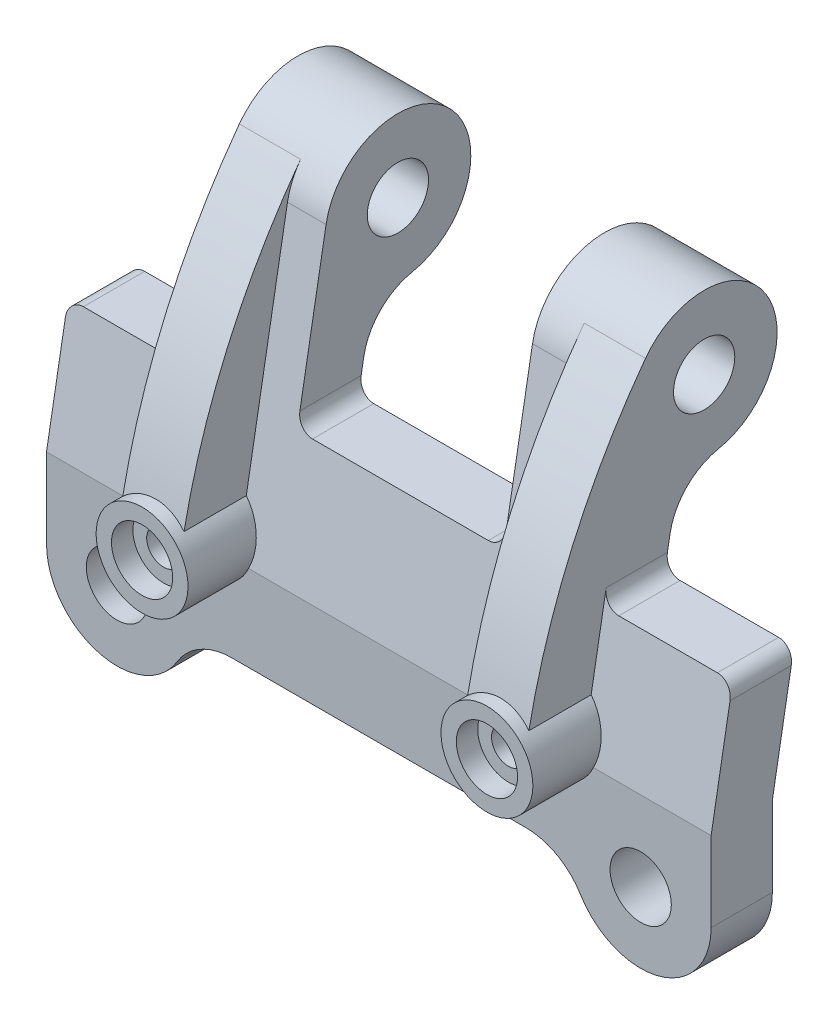
SolidWorks part; units mm, degrees
ref_plane "Front Plane" through (0, 0, 0) normal (0, 0, 1) x (1, 0, 0)
ref_plane "Top Plane" through (0, 0, 0) normal (0, 1, 0) x (1, 0, 0)
ref_plane "Right Plane" through (0, 0, 0) normal (1, 0, 0) x (0, 0, -1)
sketch "Sketch2" plane through (0, 0, 0) normal (1, 0, 0) x (0, 0, -1)
  line L0 (2.8983, 8.382) -> (0.3583, 8.382) construction
  line L1 (0.3583, 8.382) -> (0, 6.35)
  line L2 (0, 6.35) -> (0, 0)
  line L3 (0, 0) -> (2.54, 0)
  line L7 (2.8983, 8.382) -> (2.54, 6.35)
  line L8 (2.54, 6.35) -> (2.54, 0)
  line L9 (0.3583, 8.382) -> (2.9112, 22.86)
  line L10 (2.8983, 8.382) -> (5.4512, 22.86)
  line L11 (2.9112, 22.86) -> (5.4512, 22.86)
  point P3 (0, 0)
  dimension "D1" = 2.54
  dimension "D2" = 100
  dimension "D3" = 8.382
  dimension "D4" = 6.35
  dimension "D5" = 22.86
extrude "Boss-Extrude1" add sketch "Sketch2" along normal mid plane 27.559
sketch "Sketch3" plane through (0, 0, 0) normal (0, 0, 1) x (1, 0, 0)
  line L0 (-6.0931, 2.794) -> (6.0931, 2.794)
  line L2 (13.7795, 3.0391) -> (13.7795, 6.35) construction
  line L3 (13.7795, 6.35) -> (-13.7795, 6.35) construction
  line L4 (-13.7795, 6.35) -> (-13.7795, 3.0391) construction
  line L6 (13.7795, 22.86) -> (13.7795, 6.35) construction
  line L7 (-13.7795, 22.86) -> (-13.7795, 6.35) construction
  line L8 (0, 2.794) -> (0, 0) construction
  line L9 (13.7795, 0) -> (-13.7795, 0) construction
  line L10 (13.7795, 6.35) -> (-13.7795, 6.35) construction
  line L11 (-13.7795, 6.35) -> (-13.7795, 0) construction
  line L12 (10.8585, 3.0391) -> (13.7795, 3.0391) construction
  line L13 (13.7795, 3.0391) -> (14.4145, 3.0391)
  line L14 (14.4145, 3.0391) -> (14.4145, -0.635)
  line L15 (14.4145, -0.635) -> (-14.4145, -0.635)
  line L16 (-14.4145, -0.635) -> (-14.4145, 3.0391)
  line L17 (-14.4145, 3.0391) -> (-13.7795, 3.0391)
  line L18 (13.7795, 6.35) -> (13.7795, 0) construction
  line L19 (-14.4145, 11.43) -> (-8.4201, 11.43)
  line L20 (-8.4201, 11.43) -> (-8.4201, 22.86)
  line L21 (13.7795, 22.86) -> (-13.7795, 22.86) construction
  line L22 (-8.4201, 22.86) -> (-4.2799, 22.86)
  line L23 (-4.2799, 22.86) -> (-4.2799, 11.43)
  line L24 (-4.2799, 11.43) -> (4.2799, 11.43)
  line L25 (4.2799, 11.43) -> (4.2799, 22.86)
  line L26 (4.2799, 22.86) -> (8.4201, 22.86)
  line L27 (8.4201, 22.86) -> (8.4201, 11.43)
  line L28 (8.4201, 11.43) -> (14.4145, 11.43)
  line L29 (14.4145, 11.43) -> (14.4145, 23.495)
  line L30 (14.4145, 23.495) -> (-14.4145, 23.495)
  line L31 (-14.4145, 23.495) -> (-14.4145, 11.43)
  arc A0 (8.3645, 1.5186) -> (6.0931, 2.794) centre (6.0931, 0.1338) ccw
  arc A1 (8.3645, 1.5186) -> (13.7795, 3.0391) centre (10.8585, 3.0391) ccw
  arc A2 (-13.7795, 3.0391) -> (-8.3645, 1.5186) centre (-10.8585, 3.0391) ccw
  arc A3 (-6.0931, 2.794) -> (-8.3645, 1.5186) centre (-6.0931, 0.1338) ccw
  circle A4 centre (-10.8585, 3.0391) radius 1.27
  circle A5 centre (10.8585, 3.0391) radius 1.27
  dimension "D2" = 2.921
  dimension "D3" = 2.921
  dimension "D15" = 2.54
  dimension "D16" = 2.54
  dimension "D1" = 2.794
  dimension "D4" = 12.1862
  dimension "D5" = 3.3109
  dimension "D6" = 3.3109
  dimension "D7" = 0.635
  dimension "D8" = 0.635
  dimension "D9" = 0.635
  dimension "D10" = 0.635
  dimension "D11" = 5.3594
  dimension "D12" = 5.3594
  dimension "D13" = 4.1402
  dimension "D14" = 4.1402
  dimension "D17" = 8.636
extrude "Cut-Extrude1" cut sketch "Sketch3" against normal through all
sketch "Sketch4" plane through (0, 0, 0) normal (1, 0, 0) x (0, 0, -1)
  line L5 (0.8957, 11.43) -> (2.9112, 22.86) construction
  circle A0 centre (5.0709, 17.6911) radius 1.27 construction
  circle A3 centre (5.0709, 17.6911) radius 3.0245
  dimension "D2" = 2.5309
  dimension "D3" = 2.54
  dimension "D1" = 11.3411
extrude "Boss-Extrude3" add sketch "Sketch4" along normal up to surface and the other way up to surface contours A3 up to face at (13.7795, 6.9397, -1.5686) other way up to face at (-13.7795, 6.9397, -1.5686)
sketch "Sketch5" plane through (13.7795, 0, 0) normal (1, 0, 0) x (0, 0, -1)
  line L0 (2.0923, 18.2163) -> (2.9112, 22.86) construction
  line L1 (5.4512, 22.86) -> (5.073, 20.7156) construction
  line L2 (5.4512, 22.86) -> (2.9112, 22.86) construction
  line L3 (2.0923, 18.2163) -> (2.9112, 22.86)
  line L4 (5.4512, 22.86) -> (2.9112, 22.86)
  line L5 (5.4512, 22.86) -> (5.073, 20.7156)
  arc A0 (2.0923, 18.2163) -> (5.073, 20.7156) centre (5.0709, 17.6911) cw
  circle A2 centre (5.0709, 17.6911) radius 1.27
  dimension "D1" = 2.54
extrude "Cut-Extrude2" cut sketch "Sketch5" against normal blind 27.686
sketch "Sketch6" plane through (0, 0, 0) normal (0, 0, 1) x (1, 0, 0)
  line L0 (-8.4201, 18.2163) -> (-8.4201, 11.43) construction
  line L1 (-8.4201, 14.6666) -> (-13.7795, 14.6666)
  line L2 (-8.4201, 14.6666) -> (-8.4201, 20.7156)
  line L3 (-8.4201, 20.7156) -> (-13.7795, 20.7156)
  line L4 (-13.7795, 14.6666) -> (-13.7795, 20.7156)
  line L5 (-13.7795, 14.6666) -> (13.7795, 14.6666) construction
  line L6 (-4.2799, 11.43) -> (-4.2799, 18.2163) construction
  line L7 (-4.2799, 14.6666) -> (4.2799, 14.6666)
  line L8 (-4.2799, 14.6666) -> (-4.2799, 20.7156)
  line L9 (-4.2799, 20.7156) -> (4.2799, 20.7156)
  line L10 (4.2799, 14.6666) -> (4.2799, 20.7156)
  line L11 (13.7795, 20.7156) -> (-13.7795, 20.7156) construction
  line L12 (8.4201, 11.43) -> (8.4201, 18.2163) construction
  line L13 (8.4201, 14.6666) -> (13.7795, 14.6666)
  line L14 (8.4201, 14.6666) -> (8.4201, 20.7156)
  line L15 (8.4201, 20.7156) -> (13.7795, 20.7156)
  line L16 (13.7795, 14.6666) -> (13.7795, 20.7156)
  line L17 (4.2799, 18.2163) -> (4.2799, 14.8483) construction
extrude "Cut-Extrude3" cut sketch "Sketch6" against normal through all
fillet "Fillet1" radius 2.54 1 edges at (6.35, 14.8483, -4.0385)
sketch "Sketch7" plane through (-8.4201, 0, 0) normal (-1, 0, 0) x (0, 0, 1)
  line L1 (0, 6.35) -> (2.54, 6.35)
  line L2 (-2.0923, 18.2163) -> (0, 6.35)
  arc A0 (-2.6368, 19.4863) -> (2.54, 6.35) centre (-24.731, 3.1911) cw
  arc A1 (-2.0923, 18.2163) -> (-5.661, 14.7248) centre (-5.0709, 17.6911) ccw construction
  arc A2 (-2.0923, 18.2163) -> (-2.6368, 19.4863) centre (-5.0709, 17.6911) ccw
  point P0 (-2.6746, 19.2824)
  point P8 (0, 0)
  dimension "D1" = 2.54
  dimension "D2" = 1.27
extrude "Boss-Extrude5" add sketch "Sketch7" against normal blind 2.54
mirror "Mirror1" about plane through (0, 0, 0) normal (1, 0, 0) of "Boss-Extrude5"
sketch "Sketch8" plane through (0, 0, -2.54) normal (0, 0, -1) x (-1, 0, 0)
  line L0 (7.1501, 6.35) -> (7.1501, 7.112) construction
  line L1 (5.8801, 6.35) -> (8.4201, 6.35) construction
  line L2 (-7.1501, 6.35) -> (-7.1501, 7.112) construction
  line L3 (-5.8801, 6.35) -> (-8.4201, 6.35) construction
  circle A0 centre (7.1501, 7.112) radius 1.905
  circle A1 centre (-7.1501, 7.112) radius 1.905
  point P6 (7.1501, 6.6164)
  point P11 (0, 0)
  point P12 (7.1501, 6.8646)
  dimension "D1" = 3.81
  dimension "D2" = 0.762
extrude "Boss-Extrude6" add sketch "Sketch8" against normal blind 5.207
hole_wizard "CBORE for #00 Binding Head Machine Screw1" positions "Sketch13" profile "Sketch15" counterbore size "#00" standard "ANSI Inch"
sketch "Sketch13" plane through (0, 0, 2.667) normal (0, 0, 1) x (1, 0, 0)
  circle A0 centre (-7.1501, 7.112) radius 1.905 construction
  point P0 (-7.1501, 7.112)
  point P6 (7.1501, 7.112)
sketch "Sketch15" plane through (-7.1501, 7.112, 2.667) normal (1, 0, 0) x (0, -1, 0)
  line L0 (0, 0) -> (0, 4.2297)
  line L1 (0, 4.2297) -> (0.6985, 3.81)
  line L2 (0.6985, 3.81) -> (0.6985, 0.889)
  line L3 (0.6985, 0.889) -> (1.27, 0.889)
  line L4 (1.27, 0.889) -> (1.27, 0)
  line L5 (1.27, 0) -> (0, 0)
  line L10 (0, 4.2297) -> (-0.6985, 3.81) construction
  line L11 (0, -6.35) -> (0, 107.95) construction
  dimension "Hole Dia." = 1.397
  dimension "Hole Depth" = 3.81
  dimension "C'Bore Dia." = 2.54
  dimension "C'Bore Depth" = 0.889
  dimension "Drill Angle" = 118
fillet "Fillet3" radius 0.635 6 edges at (13.7795, 11.43, -2.1657) (8.4201, 11.43, -2.1657) (-4.2799, 11.43, -2.1657) (4.2799, 11.43, -2.1657) (-8.4201, 11.43, -2.1657) (-13.7795, 11.43, -2.1657)
